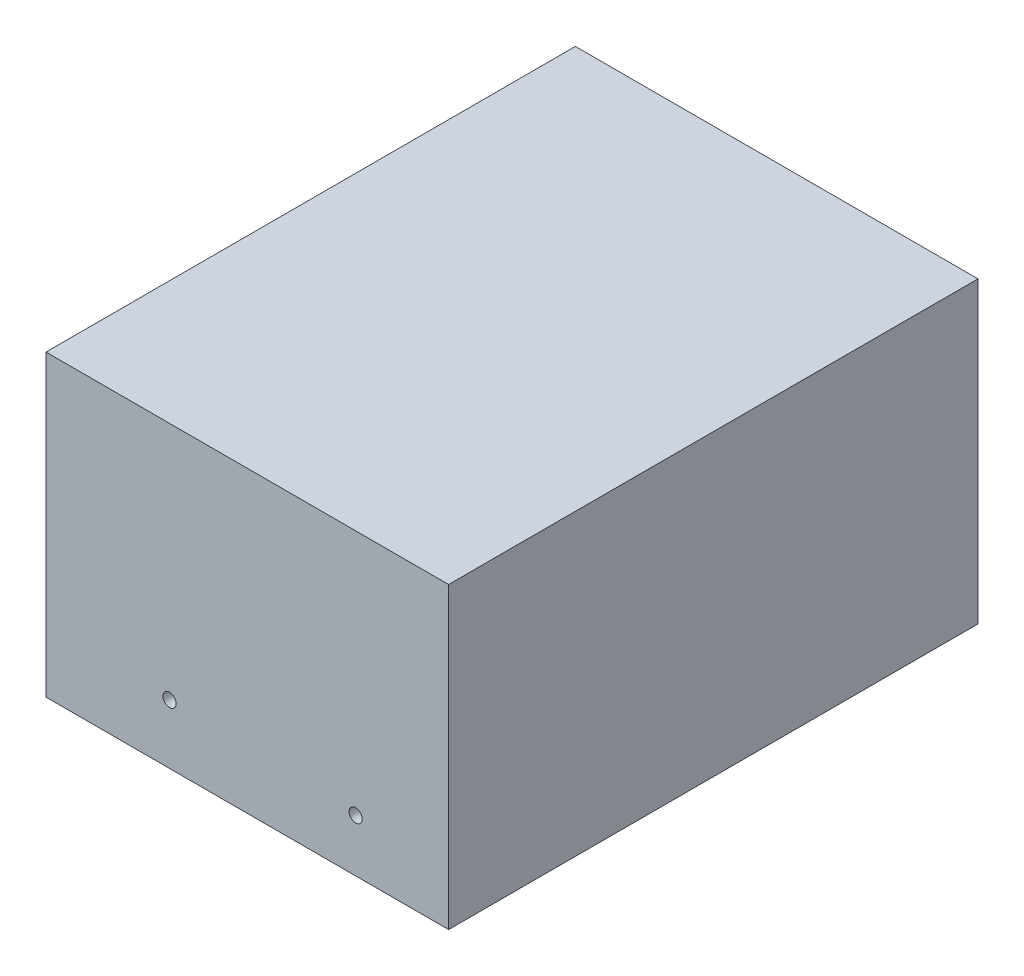
SolidWorks part; units mm, degrees
ref_plane "Front Plane" through (0, 0, 0) normal (0, 0, 1) x (1, 0, 0)
ref_plane "Top Plane" through (0, 0, 0) normal (0, 1, 0) x (1, 0, 0)
ref_plane "Right Plane" through (0, 0, 0) normal (1, 0, 0) x (0, 0, -1)
sketch "Sketch1" plane through (0, 0, 0) normal (0, 0, 1) x (1, 0, 0)
  line L0 (0, 0) -> (48.9, 0)
  line L1 (48.9, 0) -> (48.9, -36.3)
  line L2 (48.9, -36.3) -> (0, -36.3)
  line L3 (0, -36.3) -> (0, 0)
  dimension "D1" = 48.9
  dimension "D2" = 36.3
extrude "Boss-Extrude1" add sketch "Sketch1" along normal blind 26
sketch "Sketch3" plane through (0, 0, 0) normal (0, 0, -1) x (-1, 0, 0)
  line L0 (-48.9, -18.15) -> (-46.92, -18.15) construction
  line L1 (-48.9, -36.3) -> (-48.9, 0) construction
  line L2 (0, -18.15) -> (-1.98, -18.15) construction
  line L3 (0, 0) -> (0, -36.3) construction
  line L4 (-24.45, 0) -> (-24.45, -1.98) construction
  line L5 (-48.9, 0) -> (0, 0) construction
  line L6 (-24.45, -36.3) -> (-24.45, -34.32) construction
  line L7 (0, -36.3) -> (-48.9, -36.3) construction
  line L8 (-24.45, -1.98) -> (-46.92, -1.98)
  line L9 (-46.92, -1.98) -> (-46.92, -34.32)
  line L10 (-46.92, -34.32) -> (-1.98, -34.32)
  line L11 (-1.98, -34.32) -> (-1.98, -1.98)
  line L12 (-1.98, -1.98) -> (-24.45, -1.98)
  dimension "D1" = 1.98
  dimension "D2" = 1.98
  dimension "D3" = 1.98
  dimension "D4" = 1.98
extrude "Cut-Extrude1" cut sketch "Sketch3" against normal blind 24.5
sketch "Sketch4" plane through (0, 0, 24.5) normal (0, 0, -1) x (-1, 0, 0)
  line L8 (-46.92, -34.32) -> (-1.98, -34.32) construction
  line L9 (-39.66, -1.98) -> (-37.51, -1.98)
  line L10 (-1.98, -1.98) -> (-46.92, -1.98) construction
  line L11 (-37.51, -1.98) -> (-37.51, -4.33)
  line L12 (-37.51, -4.33) -> (-39.66, -4.33)
  line L13 (-39.66, -4.33) -> (-39.66, -1.98)
  line L14 (-46.92, -1.98) -> (-46.92, -34.32) construction
  line L16 (-37.51, -1.98) -> (-30.56, -1.98) construction
  line L17 (-30.56, -1.98) -> (-30.56, -4.33)
  line L18 (-30.56, -4.33) -> (-28.41, -4.33)
  line L19 (-28.41, -4.33) -> (-28.41, -1.98)
  line L20 (-28.41, -1.98) -> (-30.56, -1.98)
  line L21 (-28.41, -1.98) -> (-21.46, -1.98) construction
  line L22 (-21.46, -1.98) -> (-21.46, -4.33)
  line L23 (-21.46, -4.33) -> (-19.31, -4.33)
  line L24 (-19.31, -4.33) -> (-19.31, -1.98)
  line L25 (-19.31, -1.98) -> (-21.46, -1.98)
  line L26 (-19.31, -1.98) -> (-12.36, -1.98) construction
  line L27 (-12.36, -1.98) -> (-12.36, -4.33)
  line L28 (-12.36, -4.33) -> (-10.21, -4.33)
  line L29 (-10.21, -4.33) -> (-10.21, -1.98)
  line L30 (-10.21, -1.98) -> (-12.36, -1.98)
  dimension "D3" = 7.26
  dimension "D4" = 2.15
  dimension "D5" = 2.35
  dimension "D6" = 6.95
  dimension "D7" = 2.15
  dimension "D8" = 6.95
  dimension "D9" = 2.15
  dimension "D10" = 6.95
  dimension "D11" = 2.15
  dimension "D12" = 2.35
  dimension "D13" = 2.35
  dimension "D14" = 2.35
extrude "Boss-Extrude3" add sketch "Sketch4" along normal up to surface (24.5 mm away) up to face at (24.45, -18.15, 0)
sketch "Sketch5" plane through (0, 0, 24.5) normal (0, 0, -1) x (-1, 0, 0)
  line L0 (-46.92, -34.32) -> (-1.98, -34.32) construction
  line L1 (-11.04, -17.37) -> (-37.86, -17.37)
  line L2 (-11.04, -17.37) -> (-11.04, -20.32)
  line L3 (-11.04, -20.32) -> (-37.86, -20.32)
  line L4 (-37.86, -17.37) -> (-37.86, -20.32)
  line L5 (-11.04, -17.37) -> (-37.86, -20.32) construction
  line L6 (-11.04, -20.32) -> (-37.86, -17.37) construction
  point P0 (-24.45, -18.15)
  dimension "D1" = 26.82
  dimension "D2" = 2.95
  dimension "D3" = 14
extrude "Boss-Extrude4" add sketch "Sketch5" along normal blind 16.12
sketch "Sketch6" plane through (0, 0, 8.38) normal (0, 0, -1) x (-1, 0, 0)
  line L0 (-37.86, -20.32) -> (-35.49, -20.32) construction
  line L1 (-37.86, -20.32) -> (-11.04, -20.32) construction
  line L3 (-35.49, -20.32) -> (-35.49, -19.58)
  line L4 (-35.49, -19.58) -> (-30.92, -19.58)
  line L5 (-30.92, -19.58) -> (-30.92, -20.32)
  line L6 (-30.92, -20.32) -> (-35.49, -20.32)
  line L7 (-30.92, -20.32) -> (-28.55, -20.32) construction
  line L11 (-20.55, -20.32) -> (-28.55, -20.32)
  line L12 (-24.45, -17.37) -> (-24.45, -24.8823) construction
  line L13 (-11.04, -17.37) -> (-37.86, -17.37) construction
  line L14 (-17.98, -20.32) -> (-13.41, -20.32)
  line L15 (-13.41, -20.32) -> (-13.41, -19.58)
  line L16 (-17.98, -19.58) -> (-17.98, -20.32)
  line L17 (-13.41, -19.58) -> (-17.98, -19.58)
  line L18 (-37.86, -18.845) -> (-11.04, -18.845) construction
  line L19 (-37.86, -17.37) -> (-37.86, -20.32) construction
  line L20 (-11.04, -20.32) -> (-11.04, -17.37) construction
  line L21 (-13.41, -17.37) -> (-13.41, -18.11)
  line L22 (-13.41, -18.11) -> (-17.98, -18.11)
  line L23 (-17.98, -17.37) -> (-13.41, -17.37)
  line L24 (-17.98, -18.11) -> (-17.98, -17.37)
  line L27 (-20.55, -17.37) -> (-28.55, -17.37)
  line L29 (-30.92, -18.11) -> (-30.92, -17.37)
  line L30 (-30.92, -17.37) -> (-35.49, -17.37)
  line L31 (-35.49, -18.11) -> (-30.92, -18.11)
  line L32 (-35.49, -17.37) -> (-35.49, -18.11)
  line L33 (-28.55, -20.32) -> (-28.55, -19.58)
  line L34 (-28.55, -19.58) -> (-20.55, -19.58)
  line L35 (-20.55, -19.58) -> (-20.55, -20.32)
  line L36 (-28.55, -17.37) -> (-28.55, -18.11)
  line L37 (-28.55, -18.11) -> (-20.55, -18.11)
  line L38 (-20.55, -18.11) -> (-20.55, -17.37)
  dimension "D1" = 2.37
  dimension "D2" = 0.74
  dimension "D3" = 4.57
  dimension "D4" = 2.37
extrude "Cut-Extrude2" cut sketch "Sketch6" against normal blind 16.12
sketch "Sketch7" plane through (48.9, 0, 0) normal (1, 0, 0) x (0, 0, -1)
  line L0 (-26, 0) -> (-64.3, 0)
  line L1 (-64.3, 0) -> (-64.3, -36.3)
  line L2 (-64.3, -36.3) -> (-26, -36.3)
  line L3 (-26, -36.3) -> (-26, 0)
  dimension "D1" = 38.3
extrude "Boss-Extrude5" add sketch "Sketch7" against normal up to surface (48.9 mm away) up to face at (0, -18.15, 13)
sketch "Sketch8" plane through (0, 0, 24.5) normal (0, 0, -1) x (-1, 0, 0)
  circle A0 centre (-37.6114, -29.9288) radius 0.9
  circle A1 centre (-15.011, -29.088) radius 0.9
  dimension "D1" = 1.8
  dimension "D2" = 1.8
extrude "Cut-Extrude3" cut sketch "Sketch8" against normal blind 11.45
sketch "Sketch9" plane through (0, 0, 35.95) normal (0, 0, -1) x (-1, 0, 0)
  circle A0 centre (-37.6114, -29.9288) radius 0.8
  circle A1 centre (-15.011, -29.088) radius 0.8
  dimension "D1" = 1.6
  dimension "D2" = 1.6
extrude "Cut-Extrude4" cut sketch "Sketch9" against normal through all
